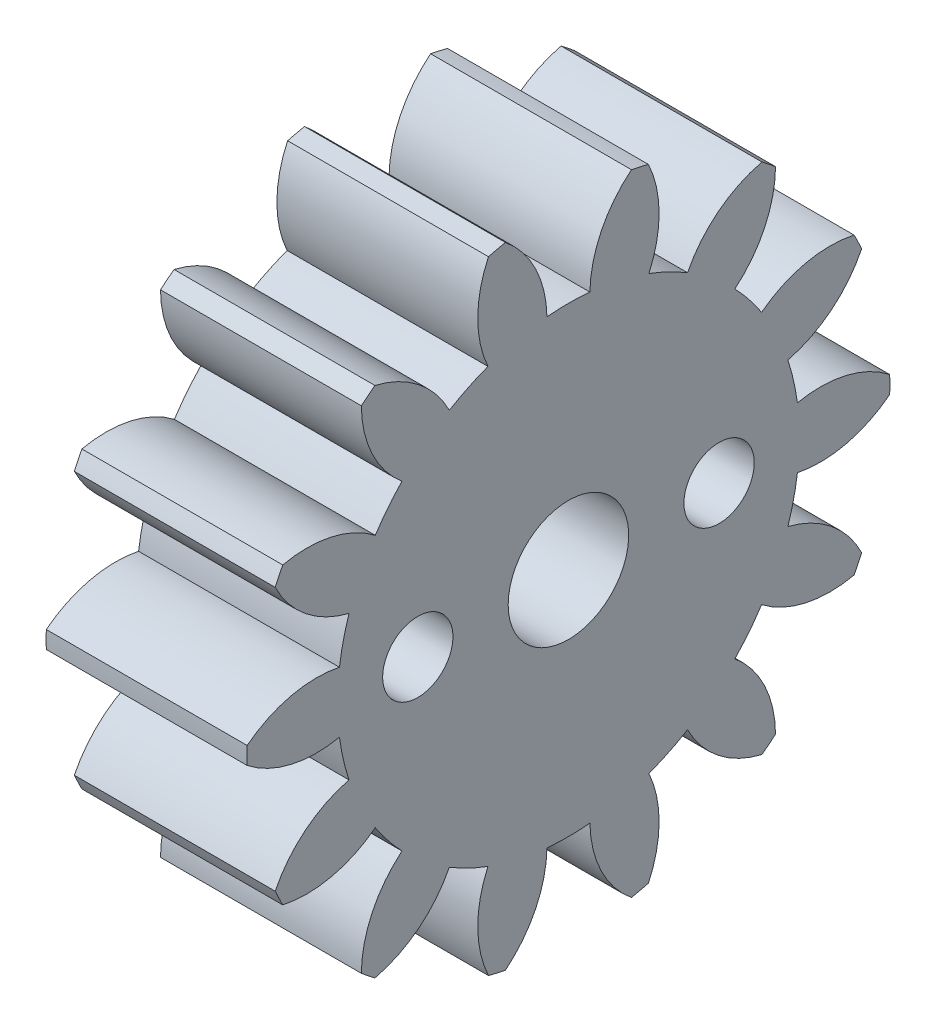
SolidWorks part; units mm, degrees
ref_plane "Plane1" through (0, 0, 0) normal (0, 0, 1) x (1, 0, 0)
ref_plane "Plane2" through (0, 0, 0) normal (0, 1, 0) x (1, 0, 0)
ref_plane "Plane3" through (0, 0, 0) normal (1, 0, 0) x (0, 0, -1)
other "Configuration Table"
sketch "HoldingSke" plane through (0, 0, 0) normal (0, 1, 0) x (1, 0, 0)
  line L0 (0, 0) -> (0.4851, -0.121)
  line L1 (-15, 0) -> (100, 0) construction
  line L2 (0, 0) -> (-2.1039, 2.3779)
  line L3 (0, 0) -> (-11.863, 4.5341)
  line L4 (0, 0) -> (8.3795, 2.0892)
  line L5 (0, 0) -> (-46.8476, -17.4728)
  line L6 (0, 0) -> (-8.2896, -5.593)
  line L7 (-2.1039, 2.3779) -> (8.6586, 51.2059)
  line L8 (-76.2, 54.61) -> (-75.2, 54.61)
  line L9 (-71.009, 38.7566) -> (-53.1078, 45.2721)
  line L10 (-76.2, 71.12) -> (104.1128, 71.12)
  line L11 (0, 0) -> (-10, 0)
  line L12 (-76.2, 101.6) -> (-76.133, 101.6)
  line L13 (24.9733, 27.94) -> (52.9518, 28.4284)
  line L14 (24.9733, 27.94) -> (24.9743, 27.94)
  line L15 (24.9733, 27.94) -> (100.4006, 29.5858)
  line L16 (-63.627, -2) -> (-12.827, -2)
  circle A0 centre (0, 0) radius 3
  circle A1 centre (0, 0) radius 11.499
  circle A2 centre (0, 0) radius 37.5
  circle A3 centre (0, 0) radius 3
  dimension "MHD" = 22.998
  dimension "Hub_dia" = 75
  dimension "Bore" = 6
  dimension "MBD" = 6
  dimension "Num_teeth" = 14
  dimension "Pitch" = 0.5
  dimension "Overall_len" = 50
  dimension "Show_teeth" = 14
  dimension "Thickness" = 10
  dimension "OAL" = 50.0001
  dimension "T_dim" = 1
  dimension "Ap" = 20
  dimension "H" = 19.05
  dimension "Pitch_radius" = 180.3128
  dimension "Width" = 10
  dimension "Backlash" = 0.067
  dimension "Addendum_fac" = 1
  dimension "Dedendum_fac" = 1.25
  dimension "Clearance_fac" = 0.25
  dimension "Dedendum_add" = 0.001
  dimension "Module" = 2
sketch "BasProSke" plane through (0, 0, 0) normal (0, 1, 0) x (1, 0, 0)
  line L0 (-10, 0) -> (60, 0) construction
  line L1 (0, 0) -> (0, 16)
  line L2 (0, 0) -> (10, 0)
  line L3 (10, 0) -> (10, 16)
  line L4 (10, 16) -> (0, 16)
  dimension "Thickness" = 10
  dimension "Diameter" = 32
revolve "Base-Revolve" add sketch "BasProSke" angle 360 about L0
sketch "TooCutSke" plane through (0, 0, 0) normal (1, 0, 0) x (0, 0, -1)
  line L1 (0, 0) -> (0, 107) construction
  line L2 (0, 0) -> (-1.6846, 13.8983) construction
  line L3 (0, 0) -> (-6.1971, 27.1511) construction
  line L4 (-1.6846, 13.8983) -> (-3.0985, 13.5756) construction
  arc A0 (1.0679, 11.4493) -> (-1.0679, 11.4493) centre (0, 0) ccw
  arc A1 (3.1634, 15.7101) -> (-3.1634, 15.7101) centre (0, 0) ccw
  circle A2 centre (0, 0) radius 14 construction
  circle A3 centre (0, 0) radius 13.1557 construction
  arc A4 (-1.0679, 11.4493) -> (-3.1634, 15.7101) centre (-6.6668, 11.3413) ccw
  arc A5 (3.1634, 15.7101) -> (1.0679, 11.4493) centre (6.6668, 11.3413) ccw
  dimension "Root_dia" = 22.998
  dimension "Overcut_dia" = 32.0508
  dimension "Pitch_dia" = 28
  dimension "Base_dia" = 26.3114
  dimension "Flank_rad" = 5.6
  dimension "Half_ang" = 12.857
  dimension "Half_CT" = 1.4503
extrude "ToothCut" cut sketch "TooCutSke" along normal through all
fillet "Breaks" [suppressed] radius 0.04
fillet "RootFillets" [suppressed] radius 0.501
pattern_circular "TeethCuts" count 14 every 25.714 about axis through (-10, 0, 0) along (1, 0, 0) of "ToothCut", "RootFillets", "Breaks"
sketch "HubNeaOneSke" plane through (0, 0, 0) normal (-1, 0, 0) x (0, 0, 1)
  circle A0 centre (0, 0) radius 11.499
  dimension "Diameter" = 22.998
extrude "HubNearOne" [suppressed] add sketch "HubNeaOneSke" along normal blind 40.0001
sketch "HubNeaBotSke" plane through (0, 0, 0) normal (-1, 0, 0) x (0, 0, 1)
  circle A0 centre (0, 0) radius 11.499
  dimension "Diameter" = 22.998
extrude "HubNearBoth" [suppressed] add sketch "HubNeaBotSke" along normal blind 20
ref_plane "FarPln" through (10, 0, 0) normal (1, 0, 0) x (0, 0, -1)
sketch "HubFarSke" plane through (10, 0, 0) normal (1, 0, 0) x (0, 0, -1)
  circle A0 centre (0, 0) radius 11.499
  dimension "Diameter" = 22.998
extrude "HubFar" [suppressed] add sketch "HubFarSke" along normal blind 20
sketch "BorSke" plane through (0, 0, 0) normal (1, 0, 0) x (0, 0, -1)
  circle A0 centre (0, 0) radius 3
  dimension "Diameter" = 6
extrude "Bore" cut sketch "BorSke" along normal mid plane 100.0001
sketch "KeySke" plane through (0, 0, 0) normal (1, 0, 0) x (0, 0, -1)
  line L0 (-1, 0) -> (-1, 4)
  line L1 (-1, 4) -> (1, 4)
  line L2 (1, 4) -> (1, 0)
  line L3 (0, 0) -> (0, 34) construction
  line L4 (-1, 0) -> (1, 0)
  dimension "Offset" = 4
  dimension "Width" = 2
extrude "Keyway" [suppressed] cut sketch "KeySke" along normal mid plane 100.0001
pattern_circular "Keyway2" [suppressed] count 2 every 90 about axis through (-10, 0, 0) along (1, 0, 0)
hole_wizard "M3 すきま穴1" positions "ｽｹｯﾁ2" profile "ｽｹｯﾁ3" hole size "M3" standard "JIS" end condition through all
sketch "ｽｹｯﾁ2" plane through (0, 0, 0) normal (-1, 0, 0) x (0, 0, 1)
  circle A0 centre (0, 0) radius 7.5
  point P0 (7.5, 0)
  point P2 (-7.5, 0)
  point P9 (6.7354, 3.7854)
  point P10 (7.7792, 0)
  point P11 (-7.7792, 0)
  point P12 (7.5, 0)
  point P13 (7.4586, -0.7869)
  point P14 (7.5, 0)
  point P15 (0, 0)
  point P16 (0, 0)
  dimension "D1" = 15
sketch "ｽｹｯﾁ3" plane through (0, 0, 7.5) normal (0, 1, 0) x (0, 0, 1)
  line L0 (0, 0) -> (0, 10)
  line L1 (0, 10) -> (1.75, 10)
  line L2 (1.75, 10) -> (1.75, 0)
  line L5 (1.75, 0) -> (0, 0)
  line L11 (0, -6.35) -> (0, 107.95) construction
  dimension "通し穴の直径" = 3.5
  dimension "通し穴の深さ" = 10
equation "' \"Module@HoldingSke\" = 6.35"
equation "' \"Num_teeth@HoldingSke\" = 12"
equation "' \"Ap@HoldingSke\" =  20"
equation "' \"Ap@HoldingSke\" = 20"
equation "' \"Width@HoldingSke\" = 0.5 * 25.4"
equation "' \"Hub_dia@HoldingSke\"= 1 * 25.4"
equation "' \"Hub_dia@HoldingSke\" = 1 * 25.4"
equation "' \"Overall_len@HoldingSke\" = 1.0 * 25.4"
equation "' \"Bore@HoldingSke\" = 0.75 * 25.4"
equation "' \"T_dim@HoldingSke\" = 0.1 * 25.4"
equation "' \"Width@KeySke\" = 0.25 * 25.4"
equation "' \"Show_teeth@HoldingSke\" = 13"
equation "' \"Backlash@HoldingSke\" = 0.009 * 25.4"
equation "' \"Addendum_fac@HoldingSke\" = 1.0"
equation "' \"Dedendum_fac@HoldingSke\" = 1.25"
equation "' \"Dedendum_add@HoldingSke\" = 0.00005 * 25.4"
equation "' \"Clearance_fac@HoldingSke\" = 0.25"
equation "\"Pitch@HoldingSke\" = 1 / \"Module@HoldingSke\""
equation "\"Overcut_dia@TooCutSke\" = (\"Num_teeth@HoldingSke\" + 2 * \"Addendum_fac@HoldingSke\") / \"Pitch@HoldingSke\" + 0.002 * 25.4"
equation "\"Pitch_dia@TooCutSke\" = \"Num_teeth@HoldingSke\" / \"Pitch@HoldingSke\""
equation "\"Base_dia@TooCutSke\" = \"Num_teeth@HoldingSke\" / \"Pitch@HoldingSke\" * cos((\"Ap@HoldingSke\"  * 3.14159265 / 180))"
equation "\"Root_dia@TooCutSke\" = (\"Num_teeth@HoldingSke\" + 2) / \"Pitch@HoldingSke\" - 2 * (\"Addendum_fac@HoldingSke\" + \"Dedendum_fac@HoldingSke\") / \"Pitch@HoldingSke\" - \"Dedendum_add@HoldingSke\" * 2"
equation "\"Half_ang@TooCutSke\" = 180 / \"Num_teeth@HoldingSke\""
equation "\"Half_CT@TooCutSke\" = \"Num_teeth@HoldingSke\" / \"Pitch@HoldingSke\" * sin((3.14159265 / 2 / \"Num_teeth@HoldingSke\")) / 2 - 7 * \"Backlash@HoldingSke\" / 4"
equation "\"Flank_rad@TooCutSke\" = \"Num_teeth@HoldingSke\" / \"Pitch@HoldingSke\" / 5"
equation "\"Radius@RootFillets\" = \"Clearance_fac@HoldingSke\" / \"Pitch@HoldingSke\" + \"Dedendum_add@HoldingSke\""
equation "\"Break_rad@Breaks\" = 0.02 / \"Pitch@HoldingSke\""
equation "\"Thickness@HoldingSke\" = \"Width@HoldingSke\""
equation "\"OAL@HoldingSke\" = \"Thickness@HoldingSke\""
equation "\"MHD@HoldingSke\" = (\"Num_teeth@HoldingSke\" + 2) / \"Pitch@HoldingSke\" - 2 * (\"Addendum_fac@HoldingSke\" + \"Dedendum_fac@HoldingSke\")  / \"Pitch@HoldingSke\" - \"Dedendum_add@HoldingSke\" * 2"
equation "\"MBD@HoldingSke\" = (\"Num_teeth@HoldingSke\" + 2) / \"Pitch@HoldingSke\" - 2 * (\"Addendum_fac@HoldingSke\" + \"Dedendum_fac@HoldingSke\")  / \"Pitch@HoldingSke\" - \"Dedendum_add@HoldingSke\" * 2 - 0.002 * 25.4"
equation "\"MHD@HoldingSke\" = ((sgn( \"MHD@HoldingSke\" - \"Hub_dia@HoldingSke\" )-1)*( \"MHD@HoldingSke\" - \"Hub_dia@HoldingSke\" ))/-2+ \"Hub_dia@HoldingSke\""
equation "\"MBD@HoldingSke\" = ((sgn( \"MBD@HoldingSke\" - \"Bore@HoldingSke\" )-1)*( \"MBD@HoldingSke\" - \"Bore@HoldingSke\" ))/-2+ \"Bore@HoldingSke\""
equation "\"OAL@HoldingSke\" = ((sgn( \"OAL@HoldingSke\" - \"Overall_len@HoldingSke\" )+1)*( \"OAL@HoldingSke\" - \"Overall_len@HoldingSke\" ))/2 + \"Overall_len@HoldingSke\" + 0.000002 * 25.4"
equation "\"Num_teeth@TeethCuts\" = int( \"Show_teeth@HoldingSke\" ) + 1"
equation "\"Num_teeth@TeethCuts\" = ((sgn( \"Num_teeth@TeethCuts\" - \"Num_teeth@HoldingSke\" )-1)*( \"Num_teeth@TeethCuts\" - \"Num_teeth@HoldingSke\" ))/-2+ \"Num_teeth@HoldingSke\""
equation "\"Num_teeth@TeethCuts\" = ((sgn( \"Num_teeth@TeethCuts\" - 2.0)+1)*( \"Num_teeth@TeethCuts\" - 2.0))/2 +2.0"
equation "\"Angle@TeethCuts\" = 360.0 / \"Num_teeth@HoldingSke\""
equation "\"Diameter@BasProSke\" = (\"Num_teeth@HoldingSke\" + 2 * \"Addendum_fac@HoldingSke\") / \"Pitch@HoldingSke\""
equation "\"Thickness@BasProSke\"  = \"Thickness@HoldingSke\""
equation "' \"Fillet_rad@BasProSke\" =  \"Thickness@HoldingSke\" * 0.05"
equation "' \"Fillet_rad@BasProSke\" = \"Thickness@HoldingSke\" * 0.05"
equation "\"MHD@HoldingSke\" = ((sgn( \"MHD@HoldingSke\" - \"Root_dia@TooCutSke\" )-1)*( \"MHD@HoldingSke\" - \"Root_dia@TooCutSke\" ))/-2+ \"Root_dia@TooCutSke\""
equation "\"Diameter@HubNeaOneSke\" = \"MHD@HoldingSke\""
equation "\"Length@HubNearOne\" = \"OAL@HoldingSke\" - \"Thickness@BasProSke\""
equation "\"Diameter@HubNeaBotSke\" = \"MHD@HoldingSke\""
equation "\"Length@HubNearBoth\" = ( \"OAL@HoldingSke\" - \"Thickness@BasProSke\" ) / 2.0"
equation "\"Thickness@FarPln\" = \"Thickness@BasProSke\""
equation "\"Diameter@HubFarSke\" = \"MHD@HoldingSke\""
equation "\"Length@HubFar\" = ( \"OAL@HoldingSke\" - \"Thickness@BasProSke\" ) / 2.0"
equation "\"Diameter@BorSke\" = \"MBD@HoldingSke\""
equation "\"D1@Bore\" = \"OAL@HoldingSke\" * 2.0"
equation "\"D1@Keyway\" = \"OAL@HoldingSke\" * 2.0"
equation "\"Offset@KeySke\" = \"T_dim@HoldingSke\" + \"MBD@HoldingSke\" / 2.0"
